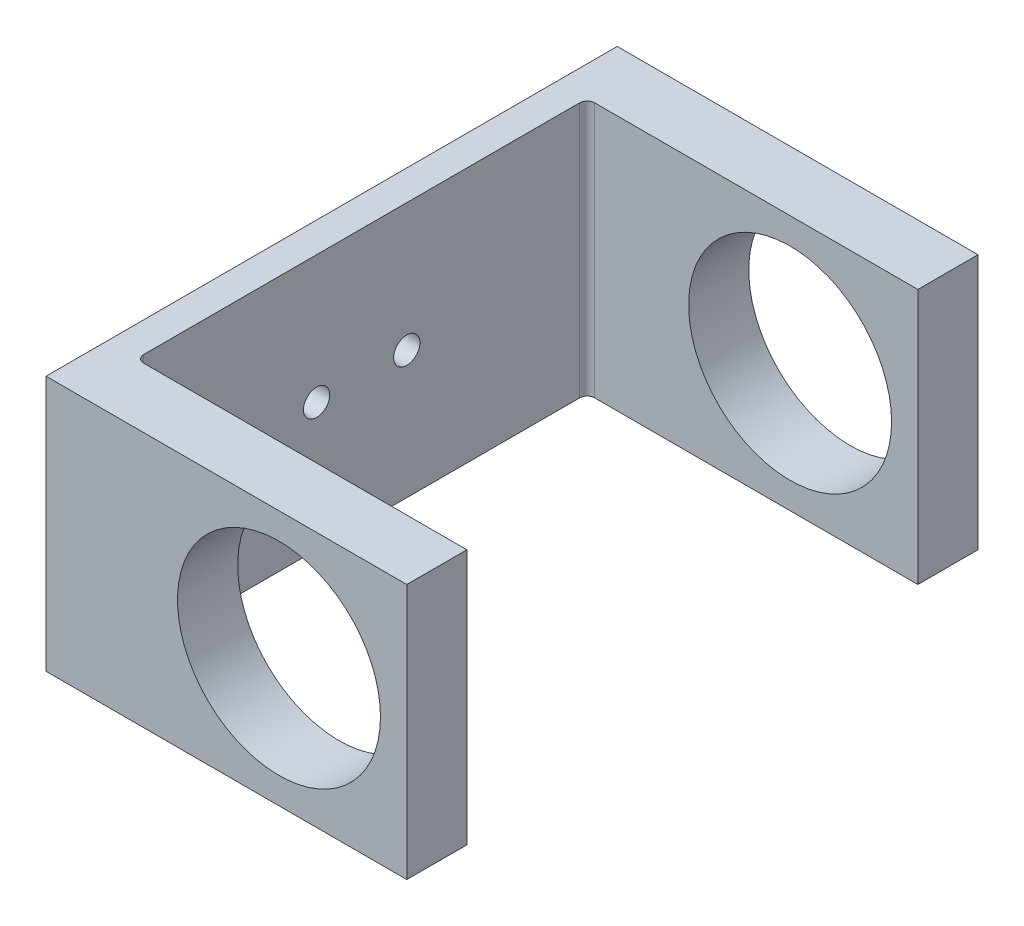
SolidWorks part; units mm, degrees
ref_plane "Front Plane" through (0, 0, 0) normal (0, 0, 1) x (1, 0, 0)
ref_plane "Top Plane" through (0, 0, 0) normal (0, 1, 0) x (1, 0, 0)
ref_plane "Right Plane" through (0, 0, 0) normal (1, 0, 0) x (0, 0, -1)
sketch "Sketch1" plane through (0, 0, 0) normal (1, 0, 0) x (0, 0, -1)
  line L0 (-30, 0) -> (30, 0) construction
  line L1 (-30, 17) -> (30, 17)
  line L2 (-30, 17) -> (-30, -17)
  line L3 (-30, -17) -> (30, -17)
  line L4 (30, 17) -> (30, -17)
  line L5 (-30, 17) -> (30, -17) construction
  line L6 (-30, -17) -> (30, 17) construction
  line L7 (0, 17) -> (0, -17) construction
  circle A0 centre (-6, 0) radius 1.75
  circle A1 centre (6, 0) radius 1.75
  point P0 (0, 0)
  dimension "D2" = 3.5
  dimension "D1" = 34
  dimension "36" = 60
  dimension "D3" = 12
extrude "Boss-Extrude1" add sketch "Sketch1" against normal blind 4
ref_plane "Plane1" through (0, 0, 30) normal (0, 0, 1) x (1, 0, 0)
sketch "Sketch3" plane through (0, 0, 30) normal (0, 0, 1) x (1, 0, 0)
  line L0 (-4, -17) -> (0, -17) construction
  line L1 (-4, 17) -> (44, 17)
  line L2 (-4, 17) -> (-4, -17)
  line L3 (-4, -17) -> (44, -17)
  line L4 (44, 17) -> (44, -17)
  line L5 (20, 17) -> (20, -17) construction
  line L6 (-4, 0) -> (44, 0) construction
  line L7 (20, 17) -> (20, -17) construction
  line L8 (0, 17) -> (0, -17) construction
  circle A0 centre (27, 0) radius 13.5
  point P7 (-2, -17)
  dimension "D1" = 27
  dimension "D2" = 48
  dimension "D3" = 27
extrude "Boss-Extrude2" add sketch "Sketch3" along normal blind 8
ref_plane "Plane4" through (0, 0, 17) normal (0, 0, -1) x (-1, 0, 0)
ref_plane "Plane5" through (0, 0, 11) normal (0, 0, -1) x (-1, 0, 0)
ref_plane "Plane6" through (0, 0, 0) normal (0, 0, -1) x (-1, 0, 0)
mirror "Mirror1" about plane through (0, 0, 0) normal (0, 0, -1) of "Boss-Extrude2"
fillet "Fillet4" radius 1 1 edges at (0, 0, 30)
fillet "Fillet5" radius 1 1 edges at (0, 0, -30)
